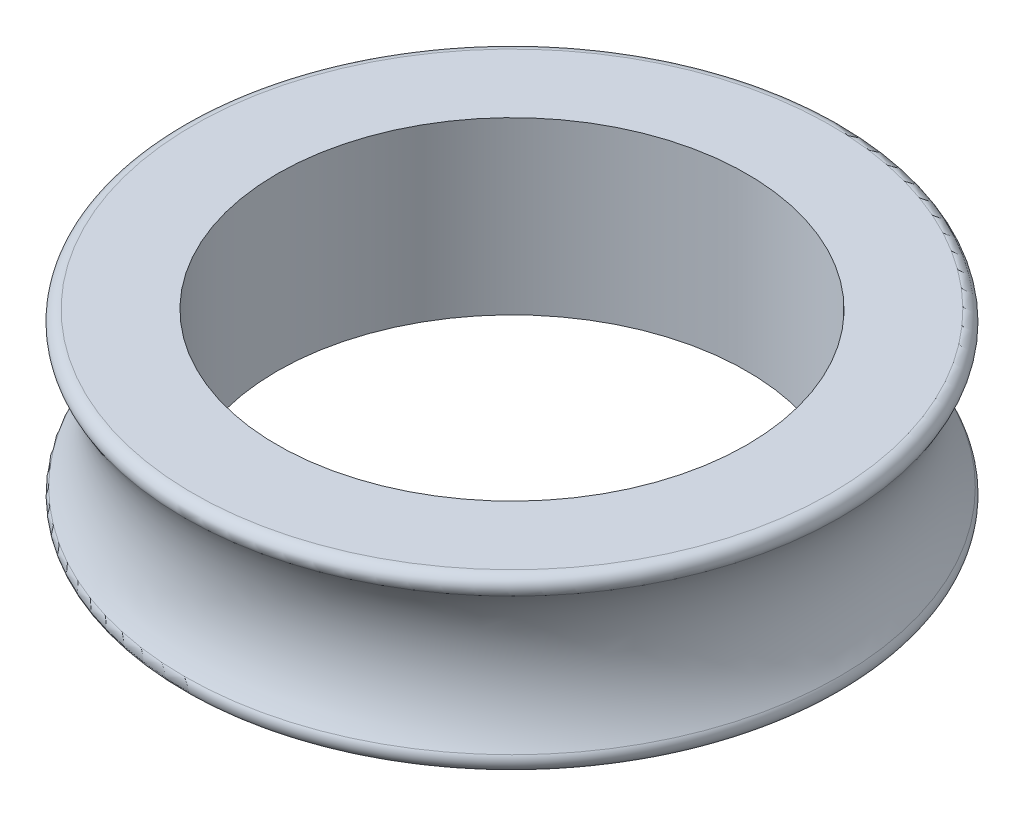
SolidWorks part; units mm, degrees
ref_plane "Front Plane" through (0, 0, 0) normal (0, 0, 1) x (1, 0, 0)
ref_plane "Top Plane" through (0, 0, 0) normal (0, 1, 0) x (1, 0, 0)
ref_plane "Right Plane" through (0, 0, 0) normal (1, 0, 0) x (0, 0, -1)
sketch "Sketch1" plane through (0, 0, 0) normal (0, 0, 1) x (1, 0, 0)
  line L0 (-16, 4) -> (-11, 4)
  line L1 (-11, 4) -> (-11, -4)
  line L2 (-11, -4) -> (-16, -4)
  line L3 (0, -1000) -> (0, 49000) construction
  arc A1 (-16, 4) -> (-16, -4) centre (-20, 0) cw
  point P5 (-11, 0)
  dimension "D4" = 5.6569
  dimension "D5" = 9
  dimension "D1" = 11
  dimension "D2" = 8
  dimension "D3" = 5
revolve "Revolve1" add sketch "Sketch1" angle 360 about L3
fillet "Fillet1" radius 0.5 2 edges at (16, -4, 0) (16, 4, 0)
